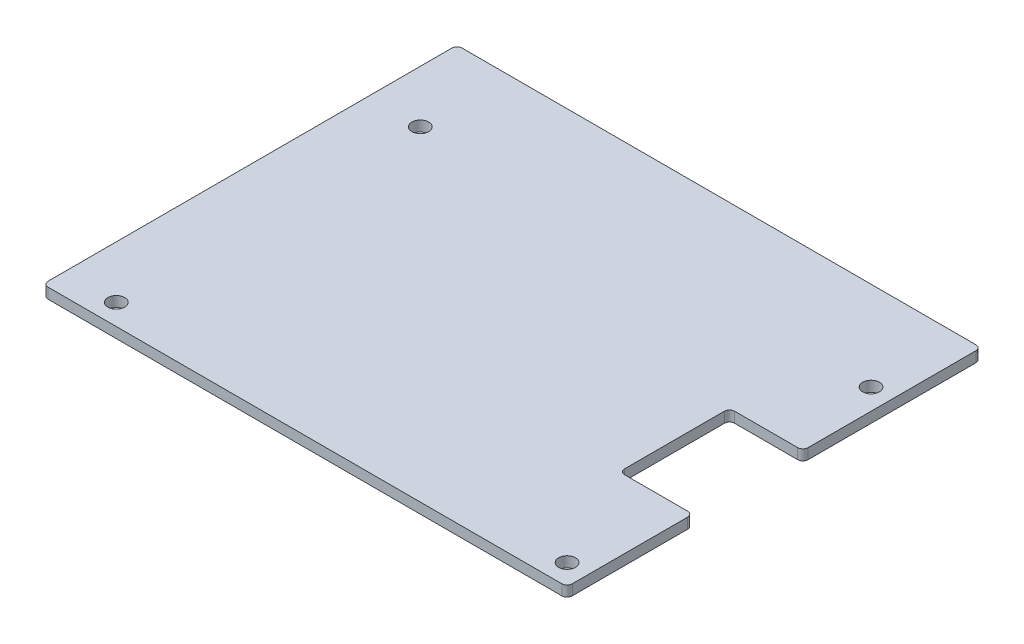
SolidWorks part; units mm, degrees
ref_plane "Front Plane" through (0, 0, 0) normal (0, 0, 1) x (1, 0, 0)
ref_plane "Top Plane" through (0, 0, 0) normal (0, 1, 0) x (1, 0, 0)
ref_plane "Right Plane" through (0, 0, 0) normal (1, 0, 0) x (0, 0, -1)
sketch "Sketch1" plane through (0, 0, 0) normal (0, 1, 0) x (1, 0, 0)
  line L1 (-50, -39.5) -> (50, -39.5)
  line L2 (-50, -39.5) -> (-50, 39.5)
  line L3 (-50, 39.5) -> (50, 39.5)
  line L4 (50, -39.5) -> (50, 39.5)
  line L5 (-50, -39.5) -> (50, 39.5) construction
  line L6 (-50, 39.5) -> (50, -39.5) construction
  point P0 (0, 0)
  dimension "D1" = 79
  dimension "D2" = 100
extrude "Boss-Extrude1" add sketch "Sketch1" along normal blind 2
sketch "Sketch2" plane through (0, 2, 0) normal (0, 1, 0) x (1, 0, 0)
  line L0 (50, -39.5) -> (50, 39.5) construction
  line L1 (50, -15.5) -> (36, -15.5)
  line L2 (50, -15.5) -> (50, 5.5)
  line L3 (50, 5.5) -> (36, 5.5)
  line L4 (36, -15.5) -> (36, 5.5)
  line L5 (-50, -39.5) -> (50, -39.5) construction
  dimension "D1" = 14
  dimension "D2" = 21
  dimension "D3" = 24
extrude "Cut-Extrude1" cut sketch "Sketch2" against normal up to next
fillet "Fillet1" radius 1 8 edges at (-50, 1, -39.5) (50, 1, -39.5) (50, 1, 39.5) (-50, 1, 39.5) (50, 1, -5.5) (36, 1, -5.5) (36, 1, 15.5) (50, 1, 15.5)
hole_wizard "M3 Clearance Hole1" positions "Sketch3" profile "Sketch4" hole size "M3" standard "ISO" end condition up to next
sketch "Sketch3" plane through (0, 2, 0) normal (0, 1, 0) x (1, 0, 0)
  line L1 (-40, 22.5) -> (46, 22.5) construction
  line L2 (-40, 22.5) -> (-40, -35.5) construction
  line L3 (-40, -35.5) -> (46, -35.5) construction
  line L4 (46, 22.5) -> (46, -35.5) construction
  line L5 (50, -38.5) -> (50, -16.5) construction
  line L6 (-49, -39.5) -> (49, -39.5) construction
  point P1 (-40, 22.5)
  point P2 (46, -35.5)
  point P241 (-40, -35.5)
  point P242 (46, 22.5)
  dimension "D1" = 4
  dimension "D2" = 4
  dimension "D3" = 86
  dimension "D4" = 58
sketch "Sketch4" plane through (-40, 2, -22.5) normal (1, 0, 0) x (0, 0, 1)
  line L0 (0, 0) -> (0, 2)
  line L1 (0, 2) -> (1.6, 2)
  line L2 (1.6, 2) -> (1.6, 0)
  line L5 (1.6, 0) -> (0, 0)
  line L11 (0, -6.35) -> (0, 107.95) construction
  dimension "Thru Hole Dia." = 3.2
  dimension "Thru Hole Depth" = 2
